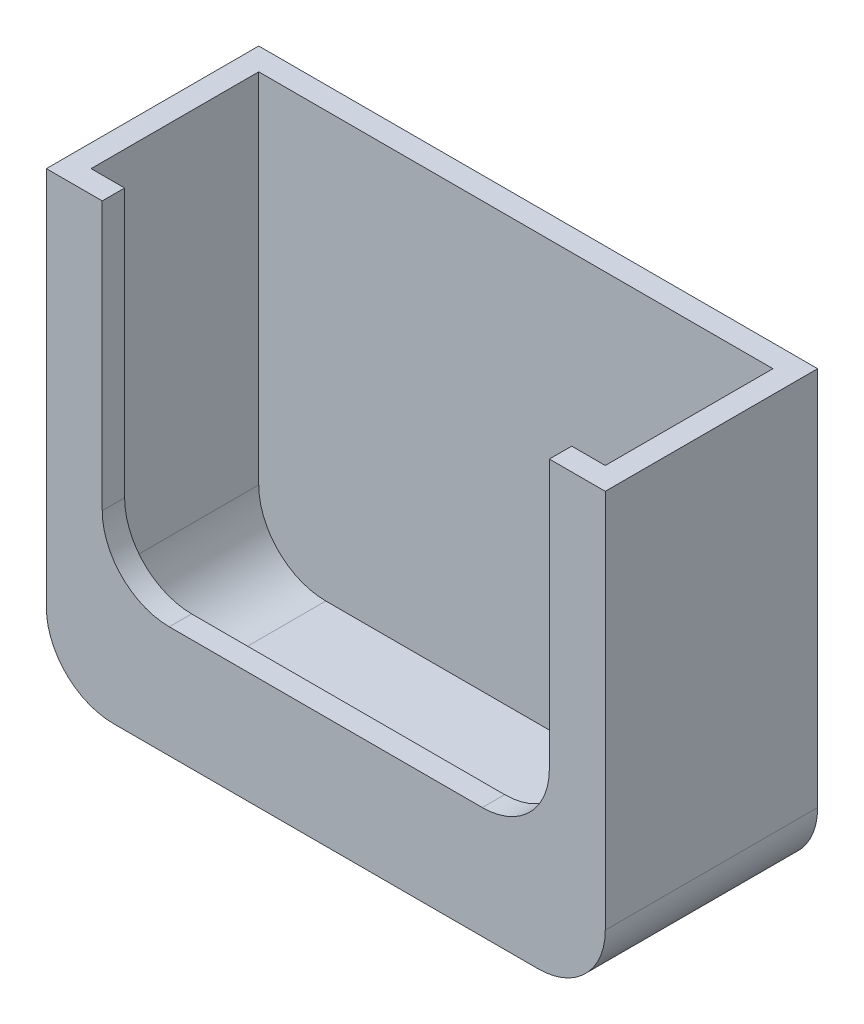
SolidWorks part; units mm, degrees
ref_plane "정면" through (0, 0, 0) normal (0, 0, 1) x (1, 0, 0)
ref_plane "윗면" through (0, 0, 0) normal (0, 1, 0) x (1, 0, 0)
ref_plane "우측면" through (0, 0, 0) normal (1, 0, 0) x (0, 0, -1)
sketch "스케치1" plane through (0, 0, 0) normal (0, 0, 1) x (1, 0, 0)
  line L1 (-25, -20) -> (25, -20)
  line L2 (-25, -20) -> (-25, 20)
  line L3 (-25, 20) -> (25, 20)
  line L4 (25, -20) -> (25, 20)
  line L5 (-25, -20) -> (25, 20) construction
  line L6 (-25, 20) -> (25, -20) construction
  point P0 (0, 0)
  dimension "D1" = 50
  dimension "D2" = 40
extrude "보스-돌출1" add sketch "스케치1" along normal blind 19
sketch "스케치2" plane through (0, 20, 0) normal (0, 1, 0) x (1, 0, 0)
  line L5 (25, -19) -> (-25, -19) construction
  line L6 (-19.5, -19) -> (19.5, -19)
  line L7 (-19.5, -19) -> (-19.5, -2)
  line L8 (-19.5, -2) -> (19.5, -2)
  line L9 (19.5, -19) -> (19.5, -2)
  line L12 (25, -19) -> (25, 0) construction
  line L13 (-23, -17) -> (23, -17)
  line L14 (-23, -17) -> (-23, -2)
  line L15 (-23, -2) -> (23, -2)
  line L16 (23, -17) -> (23, -2)
  line L17 (-23, -17) -> (23, -2) construction
  line L18 (-23, -2) -> (23, -17) construction
  line L19 (-25, -19) -> (-25, 0) construction
  point P6 (0, -2)
  point P7 (0, -9.5)
  dimension "D1" = 0
  dimension "D2" = 17
  dimension "D3" = 2
  dimension "D4" = 0
  dimension "D5" = 2
  dimension "D6" = 2
extrude "컷-돌출1" cut sketch "스케치2" against normal blind 38 contours L14 L15 L16 L13
sketch "스케치3" plane through (0, 20, 0) normal (0, 1, 0) x (1, 0, 0)
  line L0 (25, -19) -> (-25, -19) construction
  line L1 (-20, -19) -> (20, -19)
  line L2 (-20, -19) -> (-20, -17)
  line L3 (-20, -17) -> (20, -17)
  line L4 (20, -19) -> (20, -17)
  line L5 (-20, -19) -> (20, -17) construction
  line L6 (-20, -17) -> (20, -19) construction
  line L7 (-25, -19) -> (-25, 0) construction
  line L8 (25, -19) -> (25, 0) construction
  point P0 (0, -18)
  dimension "D1" = 1
  dimension "D2" = 2
  dimension "D3" = 5
  dimension "D4" = 5
extrude "컷-돌출2" cut sketch "스케치3" against normal blind 30
fillet "필렛1" radius 6 6 edges at (-25, -20, 9.5) (25, -20, 9.5) (-20, -10, 18) (20, -10, 18) (23, -18, 9.5) (-23, -18, 9.5)
